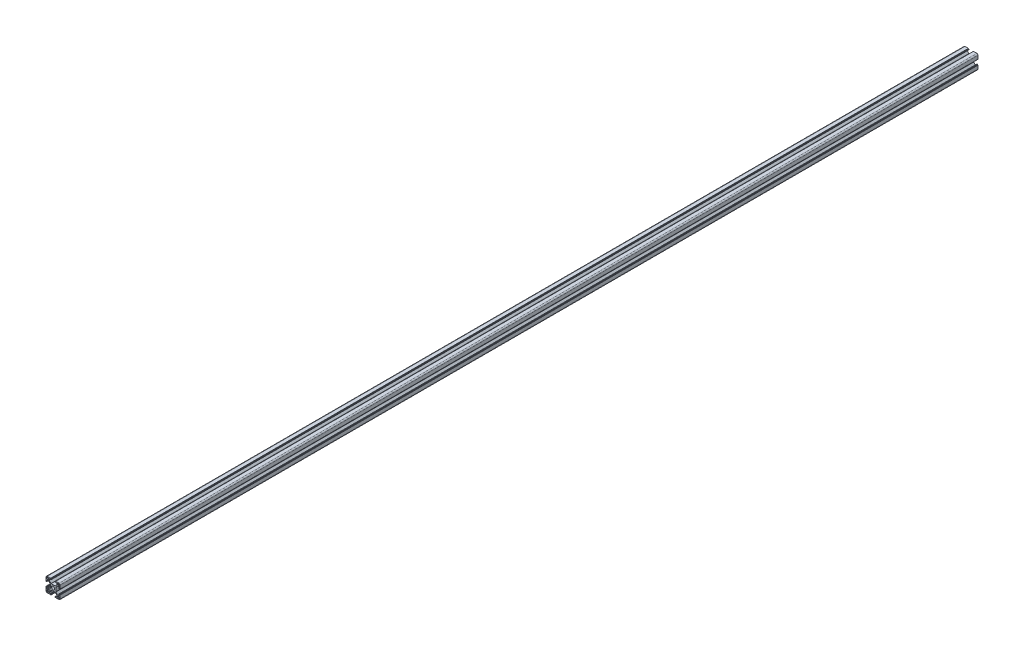
SolidWorks part; units mm, degrees
material "6063-T5"
ref_plane "Front Plane" through (0, 0, 0) normal (0, 0, 1) x (1, 0, 0)
ref_plane "Top Plane" through (0, 0, 0) normal (0, 1, 0) x (1, 0, 0)
ref_plane "Right Plane" through (0, 0, 0) normal (1, 0, 0) x (0, 0, -1)
sketch "Sketch1" plane through (0, 0, 0) normal (0, 0, 1) x (1, 0, 0)
  line L0 (0, 2.5) -> (0, 10.6)
  line L1 (2.5, 30) -> (9.5, 30)
  line L2 (30, 27.5) -> (30, 20.5)
  line L3 (27.5, 0) -> (19.4, 0)
  line L4 (19.464, 9.1128) -> (23.1303, 5.4465)
  line L5 (21.0197, 10.536) -> (24.686, 6.8697)
  line L6 (10.536, 21.0197) -> (6.8697, 24.686)
  line L7 (8.9803, 19.464) -> (5.314, 23.1303)
  line L8 (11.0663, 20.8) -> (18.9337, 20.8)
  line L9 (20.8, 18.9337) -> (20.8, 11.0663)
  line L10 (18.9337, 9.3324) -> (11.0663, 9.3324)
  line L11 (9.2, 11.0663) -> (9.2, 18.9337)
  line L12 (0, 19.4) -> (0, 27.5)
  line L13 (30, 9.5) -> (30, 2.5)
  line L14 (19.4, 27.8) -> (22.6, 27.8)
  line L15 (10.6, 27.8) -> (7.4, 27.8)
  line L16 (10.6, 0) -> (2.5, 0)
  line L17 (2.2, 20.5) -> (2.2, 22.6)
  line L18 (2.2, 9.5) -> (2.2, 7.4)
  line L19 (9.5, 2.3324) -> (7.4, 2.3324)
  line L20 (19.464, 21.0197) -> (23.1303, 24.686)
  line L21 (21.0197, 19.464) -> (24.686, 23.1303)
  line L22 (8.9803, 10.536) -> (5.314, 6.8697)
  line L23 (10.536, 9.1128) -> (6.8697, 5.4465)
  line L24 (10.8, 28.8) -> (10.8, 28)
  line L25 (19.2, 28.8) -> (19.2, 28)
  line L26 (0.2, 19.2) -> (1, 19.2)
  line L27 (0.2, 10.8) -> (1, 10.8)
  line L28 (28.8, 19.2) -> (28, 19.2)
  line L29 (28.8, 10.8) -> (28, 10.8)
  line L30 (10.8, 0.2) -> (10.8, 1.1324)
  line L31 (19.2, 0.2) -> (19.2, 1.1324)
  line L32 (20.5, 30) -> (27.5, 30)
  line L33 (27.8, 19.4) -> (27.8, 22.6)
  line L34 (27.8, 10.6) -> (27.8, 7.4)
  line L35 (20.5, 2.2) -> (22.6, 2.2)
  line L36 (6.65, 27.05) -> (6.65, 25.2163)
  line L37 (23.35, 27.05) -> (23.35, 25.2163)
  line L38 (2.95, 23.35) -> (4.7837, 23.35)
  line L39 (27.05, 23.35) -> (25.2163, 23.35)
  line L40 (2.95, 6.65) -> (4.7837, 6.65)
  line L41 (6.65, 3.0824) -> (6.65, 4.9161)
  line L42 (23.35, 2.95) -> (23.35, 4.9161)
  line L43 (27.05, 6.65) -> (25.2163, 6.65)
  line L44 (29, 10.6) -> (29, 9.9)
  line L45 (29.8, 20.3) -> (29.2, 20.3)
  line L46 (29, 20.1) -> (29, 19.4)
  line L47 (29.2, 9.7) -> (29.8, 9.7)
  line L48 (19.4, 29) -> (20.1, 29)
  line L49 (9.7, 29.8) -> (9.7, 29.2)
  line L50 (9.9, 29) -> (10.6, 29)
  line L51 (20.3, 29.2) -> (20.3, 29.8)
  line L52 (9.7, 2.1324) -> (9.7, 1.5324)
  line L53 (9.9, 1.3324) -> (10.6, 1.3324)
  line L54 (19.4, 1.3324) -> (20.1, 1.3324)
  line L55 (20.3, 1.5324) -> (20.3, 2)
  line L56 (2, 20.3) -> (1.4, 20.3)
  line L57 (1.2, 20.1) -> (1.2, 19.4)
  line L58 (1.2, 10.6) -> (1.2, 9.9)
  line L59 (1.4, 9.7) -> (2, 9.7)
  line L60 (27.55, 1.45) -> (25.8, 1.45)
  line L61 (24.8, 2.45) -> (24.8, 4.2)
  line L62 (25.8, 5.2) -> (27.55, 5.2)
  line L63 (28.55, 4.2) -> (28.55, 2.45)
  line L64 (24.8, 25.8) -> (24.8, 27.55)
  line L65 (25.8, 28.55) -> (27.55, 28.55)
  line L66 (28.55, 27.55) -> (28.55, 25.8)
  line L67 (27.55, 24.8) -> (25.8, 24.8)
  line L68 (2.45, 28.55) -> (4.2, 28.55)
  line L69 (5.2, 27.55) -> (5.2, 25.8)
  line L70 (1.45, 2.45) -> (1.45, 4.2)
  line L71 (2.45, 5.2) -> (4.2, 5.2)
  line L72 (5.2, 4.2) -> (5.2, 2.45)
  line L73 (4.2, 1.45) -> (2.45, 1.45)
  line L74 (4.2, 24.8) -> (2.45, 24.8)
  line L75 (1.45, 25.8) -> (1.45, 27.55)
  circle A0 centre (15, 15) radius 3.4
  arc A1 (25.8, 1.45) -> (24.8, 2.45) centre (25.8, 2.45) cw
  arc A2 (27.55, 1.45) -> (28.55, 2.45) centre (27.55, 2.45) ccw
  arc A3 (27.55, 5.2) -> (28.55, 4.2) centre (27.55, 4.2) cw
  arc A4 (24.8, 4.2) -> (25.8, 5.2) centre (25.8, 4.2) cw
  arc A5 (1.45, 2.45) -> (2.45, 1.45) centre (2.45, 2.45) ccw
  arc A6 (5.2, 2.45) -> (4.2, 1.45) centre (4.2, 2.45) cw
  arc A7 (4.2, 5.2) -> (5.2, 4.2) centre (4.2, 4.2) cw
  arc A8 (1.45, 4.2) -> (2.45, 5.2) centre (2.45, 4.2) cw
  arc A9 (24.8, 25.8) -> (25.8, 24.8) centre (25.8, 25.8) ccw
  arc A10 (28.55, 25.8) -> (27.55, 24.8) centre (27.55, 25.8) cw
  arc A11 (27.55, 28.55) -> (28.55, 27.55) centre (27.55, 27.55) cw
  arc A12 (24.8, 27.55) -> (25.8, 28.55) centre (25.8, 27.55) cw
  arc A13 (4.2, 28.55) -> (5.2, 27.55) centre (4.2, 27.55) cw
  arc A14 (5.2, 25.8) -> (4.2, 24.8) centre (4.2, 25.8) cw
  arc A15 (2.45, 24.8) -> (1.45, 25.8) centre (2.45, 25.8) cw
  arc A16 (2.45, 28.55) -> (1.45, 27.55) centre (2.45, 27.55) ccw
  arc A17 (30, 2.5) -> (27.5, 0) centre (27.5, 2.5) cw
  arc A18 (0, 2.5) -> (2.5, 0) centre (2.5, 2.5) ccw
  arc A19 (27.5, 30) -> (30, 27.5) centre (27.5, 27.5) cw
  arc A20 (0, 27.5) -> (2.5, 30) centre (2.5, 27.5) cw
  arc A21 (0, 10.6) -> (0.2, 10.8) centre (0.2, 10.6) cw
  arc A22 (1.2, 10.6) -> (1, 10.8) centre (1, 10.6) ccw
  arc A23 (2, 9.7) -> (2.2, 9.5) centre (2, 9.5) cw
  arc A24 (9.7, 2.1324) -> (9.5, 2.3324) centre (9.5, 2.1324) ccw
  arc A25 (10.6, 1.3324) -> (10.8, 1.1324) centre (10.6, 1.1324) cw
  arc A26 (10.6, 0) -> (10.8, 0.2) centre (10.6, 0.2) ccw
  arc A27 (19.4, 0) -> (19.2, 0.2) centre (19.4, 0.2) cw
  arc A28 (19.4, 1.3324) -> (19.2, 1.1324) centre (19.4, 1.1324) ccw
  arc A29 (20.3, 2) -> (20.5, 2.2) centre (20.5, 2) cw
  arc A30 (28, 10.8) -> (27.8, 10.6) centre (28, 10.6) ccw
  arc A31 (29, 10.6) -> (28.8, 10.8) centre (28.8, 10.6) ccw
  arc A32 (29.8, 9.7) -> (30, 9.5) centre (29.8, 9.5) cw
  arc A33 (28, 19.2) -> (27.8, 19.4) centre (28, 19.4) cw
  arc A34 (29, 19.4) -> (28.8, 19.2) centre (28.8, 19.4) cw
  arc A35 (30, 20.5) -> (29.8, 20.3) centre (29.8, 20.5) cw
  arc A36 (20.3, 29.8) -> (20.5, 30) centre (20.5, 29.8) cw
  arc A37 (19.4, 29) -> (19.2, 28.8) centre (19.4, 28.8) ccw
  arc A38 (19.2, 28) -> (19.4, 27.8) centre (19.4, 28) ccw
  arc A39 (10.8, 28) -> (10.6, 27.8) centre (10.6, 28) cw
  arc A40 (0, 19.4) -> (0.2, 19.2) centre (0.2, 19.4) ccw
  arc A41 (1.2, 19.4) -> (1, 19.2) centre (1, 19.4) cw
  arc A42 (2, 20.3) -> (2.2, 20.5) centre (2, 20.5) ccw
  arc A43 (10.6, 29) -> (10.8, 28.8) centre (10.6, 28.8) cw
  arc A44 (9.5, 30) -> (9.7, 29.8) centre (9.5, 29.8) cw
  arc A45 (1.4, 20.3) -> (1.2, 20.1) centre (1.4, 20.1) ccw
  arc A46 (20.1, 29) -> (20.3, 29.2) centre (20.1, 29.2) ccw
  arc A47 (9.7, 29.2) -> (9.9, 29) centre (9.9, 29.2) ccw
  arc A48 (29.2, 20.3) -> (29, 20.1) centre (29.2, 20.1) ccw
  arc A49 (29, 9.9) -> (29.2, 9.7) centre (29.2, 9.9) ccw
  arc A50 (20.1, 1.3324) -> (20.3, 1.5324) centre (20.1, 1.5324) ccw
  arc A51 (1.2, 9.9) -> (1.4, 9.7) centre (1.4, 9.9) ccw
  arc A52 (9.7, 1.5324) -> (9.9, 1.3324) centre (9.9, 1.5324) ccw
  arc A53 (23.35, 25.2163) -> (23.1303, 24.686) centre (22.6, 25.2163) cw
  arc A54 (25.2163, 23.35) -> (24.686, 23.1303) centre (25.2163, 22.6) ccw
  arc A55 (20.8, 18.9337) -> (21.0197, 19.464) centre (21.55, 18.9337) cw
  arc A56 (18.9337, 20.8) -> (19.464, 21.0197) centre (18.9337, 21.55) ccw
  arc A57 (6.65, 25.2163) -> (6.8697, 24.686) centre (7.4, 25.2163) ccw
  arc A58 (11.0663, 20.8) -> (10.536, 21.0197) centre (11.0663, 21.55) cw
  arc A59 (4.7837, 23.35) -> (5.314, 23.1303) centre (4.7837, 22.6) cw
  arc A60 (9.2, 18.9337) -> (8.9803, 19.464) centre (8.45, 18.9337) ccw
  arc A61 (4.7837, 6.65) -> (5.314, 6.8697) centre (4.7837, 7.4) ccw
  arc A62 (9.2, 11.0663) -> (8.9803, 10.536) centre (8.45, 11.0663) cw
  arc A63 (6.65, 4.9161) -> (6.8697, 5.4465) centre (7.4, 4.9161) cw
  arc A64 (11.0663, 9.3324) -> (10.536, 9.1128) centre (11.0663, 8.5824) ccw
  arc A65 (18.9337, 9.3324) -> (19.464, 9.1128) centre (18.9337, 8.5824) cw
  arc A66 (20.8, 11.0663) -> (21.0197, 10.536) centre (21.55, 11.0663) ccw
  arc A67 (25.2163, 6.65) -> (24.686, 6.8697) centre (25.2163, 7.4) cw
  arc A68 (23.35, 4.9161) -> (23.1303, 5.4465) centre (22.6, 4.9161) ccw
  arc A69 (7.4, 2.3324) -> (6.65, 3.0824) centre (7.4, 3.0824) cw
  arc A70 (22.6, 2.2) -> (23.35, 2.95) centre (22.6, 2.95) ccw
  arc A71 (27.8, 7.4) -> (27.05, 6.65) centre (27.05, 7.4) cw
  arc A72 (27.8, 22.6) -> (27.05, 23.35) centre (27.05, 22.6) ccw
  arc A73 (22.6, 27.8) -> (23.35, 27.05) centre (22.6, 27.05) cw
  arc A74 (2.2, 7.4) -> (2.95, 6.65) centre (2.95, 7.4) ccw
  arc A75 (2.2, 22.6) -> (2.95, 23.35) centre (2.95, 22.6) cw
  arc A76 (7.4, 27.8) -> (6.65, 27.05) centre (7.4, 27.05) ccw
  point P115 (0, 0)
extrude "Boss-Extrude1" add sketch "Sketch1" along normal blind 1940
